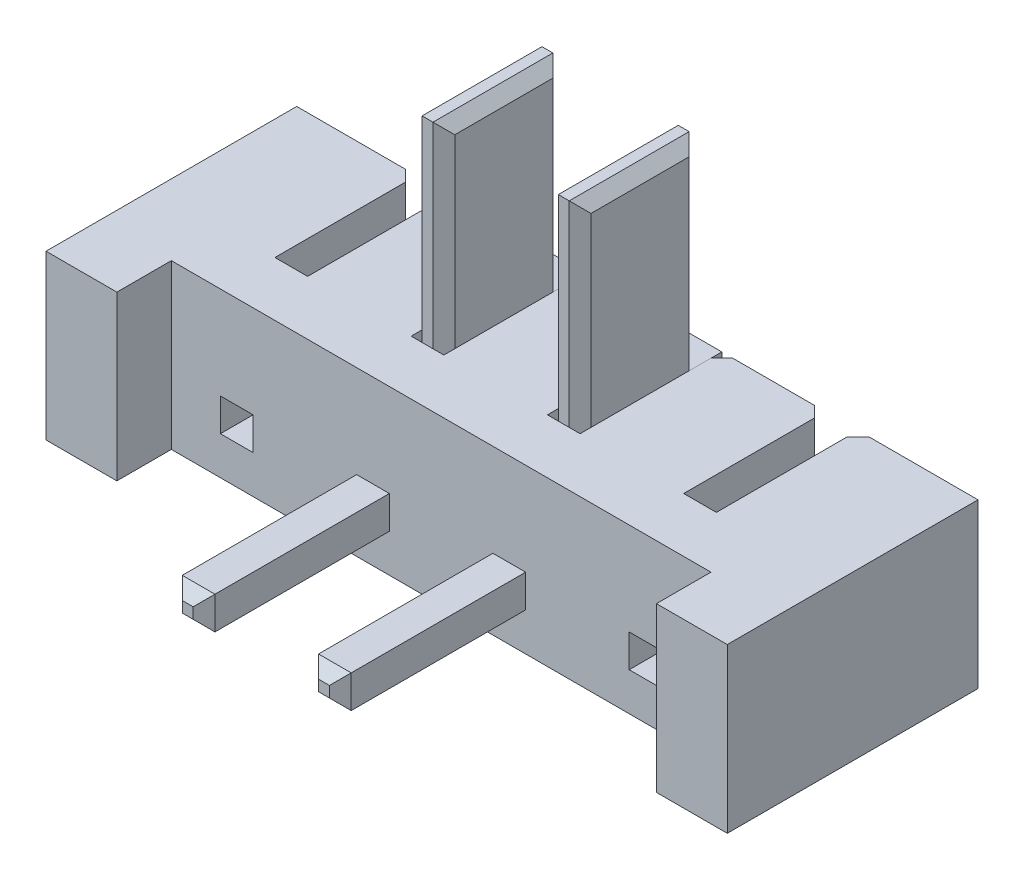
SolidWorks part; units mm, degrees
ref_plane "Спереди" through (0, 0, 0) normal (0, 0, 1) x (1, 0, 0)
ref_plane "Сверху" through (0, 0, 0) normal (0, 1, 0) x (1, 0, 0)
ref_plane "Справа" through (0, 0, 0) normal (1, 0, 0) x (0, 0, -1)
sketch "Эскиз1" plane through (0, 0, 0) normal (0, 0, 1) x (1, 0, 0)
  line L1 (0, 0) -> (12.5, 0)
  line L2 (0, 0) -> (0, 3)
  line L3 (0, 3) -> (12.5, 3)
  line L4 (12.5, 0) -> (12.5, 3)
  dimension "D1" = 12.5
  dimension "D2" = 3
extrude "Бобышка-Вытянуть1" add sketch "Эскиз1" along normal blind 4.6
sketch "Эскиз2" plane through (0, 0, 4.6) normal (0, 0, 1) x (1, 0, 0)
  line L0 (12.5, 3) -> (0, 3) construction
  line L1 (1.3, 3) -> (11.2, 3)
  line L2 (1.3, 3) -> (1.3, 0)
  line L3 (1.3, 0) -> (11.2, 0)
  line L4 (11.2, 3) -> (11.2, 0)
  line L5 (0, 0) -> (12.5, 0) construction
  line L6 (0, 3) -> (0, 0) construction
  line L7 (12.5, 0) -> (12.5, 3) construction
  dimension "D1" = 1.3
  dimension "D2" = 1.3
extrude "Вырез-Вытянуть1" cut sketch "Эскиз2" against normal blind 1
sketch "Эскиз3" plane through (0, 3, 0) normal (0, 1, 0) x (1, 0, 0)
  line L0 (6.25, 0) -> (6.25, -3.6) construction
  line L1 (12.5, 0) -> (0, 0) construction
  line L2 (11.2, -3.6) -> (1.3, -3.6) construction
  line L3 (7.2, 0) -> (7.8, 0)
  line L4 (4.7, 0) -> (5.3, 0)
  line L5 (4.7, 0) -> (4.7, -2.6)
  line L6 (4.7, -2.6) -> (5.3, -2.6)
  line L7 (5.3, 0) -> (5.3, -2.6)
  line L8 (7.2, 0) -> (7.2, -2.6)
  line L9 (7.2, -2.6) -> (7.8, -2.6)
  line L10 (7.8, 0) -> (7.8, -2.6)
  line L11 (9.7, 0) -> (10.3, 0)
  line L12 (9.7, 0) -> (9.7, -2.6)
  line L13 (9.7, -2.6) -> (10.3, -2.6)
  line L14 (10.3, 0) -> (10.3, -2.6)
  line L15 (4.7, 0) -> (5.3, 0)
  line L16 (4.7, 0) -> (4.7, -2.6)
  line L17 (4.7, -2.6) -> (5.3, -2.6)
  line L18 (5.3, 0) -> (5.3, -2.6)
  line L19 (7.2, 0) -> (7.8, 0)
  line L20 (7.2, 0) -> (7.2, -2.6)
  line L21 (7.2, -2.6) -> (7.8, -2.6)
  line L22 (7.8, 0) -> (7.8, -2.6)
  line L23 (2.2, 0) -> (2.8, 0)
  line L24 (2.2, 0) -> (2.2, -2.6)
  line L25 (2.2, -2.6) -> (2.8, -2.6)
  line L26 (2.8, 0) -> (2.8, -2.6)
  point P10 (5, 0)
  line M8 (12.5, 0) -> (0, 0)
  dimension "D1" = 0.6
  dimension "D2" = 2.6
  dimension "D3" = 1.25
  dimension "D4" = 3
  dimension "D5" = 2
extrude "Вырез-Вытянуть2" cut sketch "Эскиз3" against normal blind 2.3 contours L26 L24 L25 M8 | L7 L5 L6 M8 | L10 L8 L9 M8 | L14 L12 L13 M8
chamfer "Фаска1" distance 0.2 angle 45 8 edges at (10.3, 1.85, 0) (9.7, 1.85, 0) (7.8, 1.85, 0) (7.2, 1.85, 0) (5.3, 1.85, 0) (4.7, 1.85, 0) (2.8, 1.85, 0) (2.2, 1.85, 0)
sketch "Эскиз5" plane through (0, 0, 2.6) normal (0, 0, -1) x (-1, 0, 0)
  line L0 (-9.7, 0.7) -> (-9.7, 3) construction
  line L1 (-10.3, 0.7) -> (-9.7, 0.7)
  line L2 (-10.3, 0.7) -> (-10.3, 1.3)
  line L3 (-10.3, 1.3) -> (-9.7, 1.3)
  line L4 (-9.7, 0.7) -> (-9.7, 1.3)
  line L5 (-7.8, 0.7) -> (-7.2, 0.7)
  line L6 (-7.8, 0.7) -> (-7.8, 1.3)
  line L7 (-7.8, 1.3) -> (-7.2, 1.3)
  line L8 (-7.2, 0.7) -> (-7.2, 1.3)
  line L9 (-5.3, 0.7) -> (-4.7, 0.7)
  line L10 (-5.3, 0.7) -> (-5.3, 1.3)
  line L11 (-5.3, 1.3) -> (-4.7, 1.3)
  line L12 (-4.7, 0.7) -> (-4.7, 1.3)
  line L13 (-2.8, 0.7) -> (-2.2, 0.7)
  line L14 (-2.8, 0.7) -> (-2.8, 1.3)
  line L15 (-2.8, 1.3) -> (-2.2, 1.3)
  line L16 (-2.2, 0.7) -> (-2.2, 1.3)
  dimension "D1" = 0.6
  dimension "D2" = 4
extrude "Вырез-Вытянуть3" cut sketch "Эскиз5" against normal through all
ref_plane "Плоскость1" through (0, 6.6, 0) normal (0, 1, 0) x (1, 0, 0)
sketch "Эскиз6" plane through (0, 6.6, 0) normal (0, 1, 0) x (1, 0, 0)
  line L0 (5.3, -0.2) -> (5.3, -2.6) construction
  line L1 (4.7, -2.6) -> (5.3, -2.6)
  line L2 (4.7, -2.6) -> (4.7, -0.4)
  line L3 (4.7, -0.4) -> (5.3, -0.4)
  line L4 (5.3, -2.6) -> (5.3, -0.4)
  dimension "D1" = 2.2
extrude "Бобышка-Вытянуть2" add sketch "Эскиз6" against normal up to surface (5.9 mm away) separate body up to face at (5, 0.7, 1.2667)
sketch "Эскиз9" plane through (0, 0, 0.4) normal (0, 0, -1) x (-1, 0, 0)
  line L0 (-4.7, 0.7) -> (-4.7, 6.6) construction
  line L1 (-5.3, 0.7) -> (-4.7, 0.7)
  line L2 (-5.3, 0.7) -> (-5.3, 3)
  line L3 (-5.3, 3) -> (-4.7, 3)
  line L4 (-4.7, 0.7) -> (-4.7, 3)
  line L5 (-4.7, 3) -> (-4.5, 3) construction
extrude "Бобышка-Вытянуть8" add sketch "Эскиз9" along normal up to surface (0.4 mm away) up to face at (6.25, 1.78, 0)
sketch "Эскиз8" plane through (0, 0, 2.6) normal (0, 0, 1) x (1, 0, 0)
  line L1 (4.7, 0.7) -> (5.3, 0.7)
  line L2 (4.7, 0.7) -> (4.7, 1.3)
  line L3 (4.7, 1.3) -> (5.3, 1.3)
  line L4 (5.3, 0.7) -> (5.3, 1.3)
extrude "Бобышка-Вытянуть7" add sketch "Эскиз8" along direction (0, 0, -1) on the side of the normal blind 4.4
chamfer "Фаска2" distance 0.2 angle 45 10 edges at (4.7, 6.6, 1.5) (5.3, 6.6, 1.5) (4.7, 1, 7) (5.3, 1, 7) (5, 1.3, 7) (5, 0.7, 7)
ref_plane "Плоскость2" through (6.25, 0, 0) normal (1, 0, 0) x (0, 0, -1)
mirror "Зеркальное отражение1" about plane through (6.25, 0, 0) normal (1, 0, 0) of bodies 111
